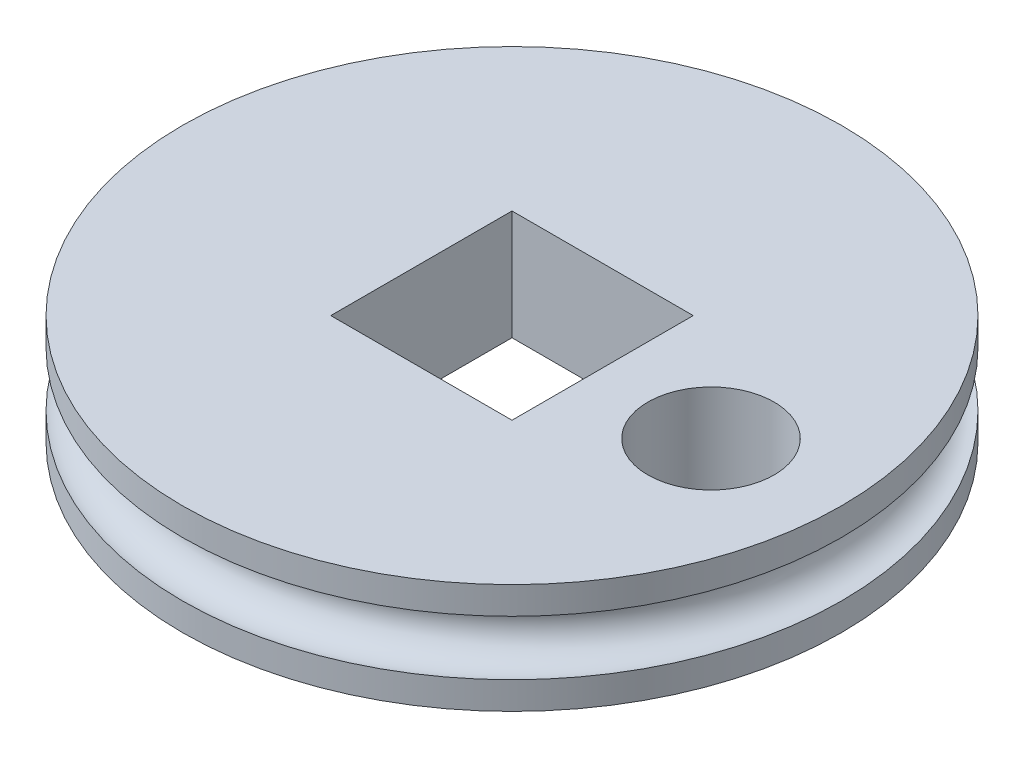
SolidWorks part; units mm, degrees
ref_plane "Ebene vorne" through (0, 0, 0) normal (0, 0, 1) x (1, 0, 0)
ref_plane "Ebene oben" through (0, 0, 0) normal (0, 1, 0) x (1, 0, 0)
ref_plane "Ebene rechts" through (0, 0, 0) normal (1, 0, 0) x (0, 0, -1)
sketch "Skizze1" plane through (0, 0, 0) normal (0, 1, 0) x (1, 0, 0)
  circle A0 centre (0, 0) radius 6
  dimension "D1" = 12
extrude "Aufsatz-Linear austragen1" add sketch "Skizze1" along normal blind 2
sketch "Skizze3" plane through (0, 2, 0) normal (0, 1, 0) x (1, 0, 0)
  line L0 (1.65, 1.65) -> (-1.65, 1.65)
  line L1 (1.65, 1.65) -> (1.65, -1.65)
  line L2 (1.65, -1.65) -> (-1.65, -1.65)
  line L3 (-1.65, 1.65) -> (-1.65, -1.65)
  line L4 (0, 0) -> (0, -3.3) construction
  line L5 (0, 0) -> (-10.1495, 0) construction
  point P8 (-1.65, 0)
  point P9 (0, -1.65)
  dimension "D1" = 1.65
  dimension "D2" = 1.65
extrude "Schnitt-Linear austragen1" cut sketch "Skizze3" against normal blind 3
sketch "Skizze4" plane through (0, 2, 0) normal (0, 1, 0) x (1, 0, 0)
  line L0 (1.65, -1.65) -> (1.65, 1.65) construction
  circle A0 centre (3.75, -0.1264) radius 1.15
  dimension "D1" = 2.3
  dimension "D2" = 2.1
extrude "Schnitt-Linear austragen2" cut sketch "Skizze4" against normal blind 3
sketch "Skizze6" plane through (0, 0, 0) normal (0, 0, 1) x (1, 0, 0)
  line L5 (-6, 2) -> (-6, 0) construction
  line L6 (-6, 1.5) -> (-6, 0.5)
  arc A0 (-6, 1.5) -> (-6, 0.5) centre (-5.8956, 1) cw
revolve "Schnitt-Rotation2" cut sketch "Skizze6" angle 360 about axis through (0, 2, 0) along (0, -1, 0)
